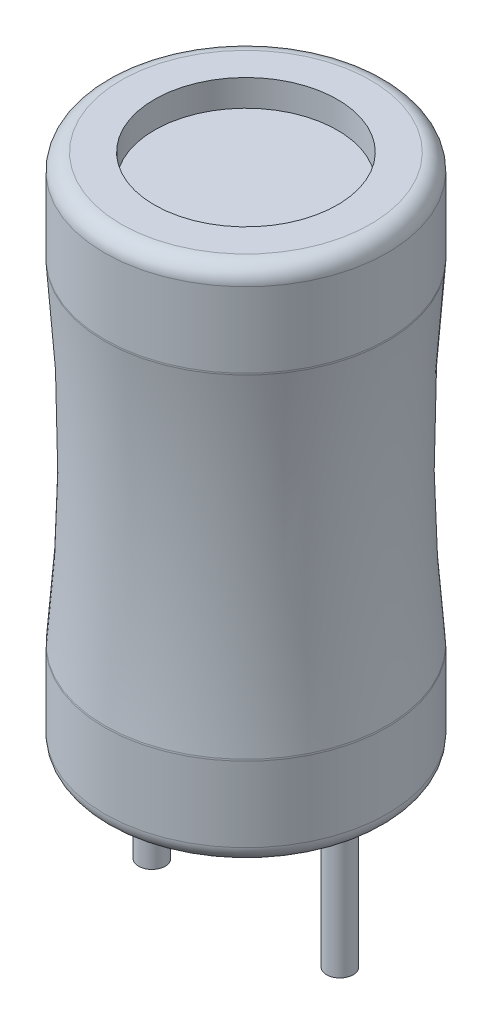
SolidWorks part; units mm, degrees
ref_plane "Front Plane" through (0, 0, 0) normal (0, 0, 1) x (1, 0, 0)
ref_plane "Top Plane" through (0, 0, 0) normal (0, 1, 0) x (1, 0, 0)
ref_plane "Right Plane" through (0, 0, 0) normal (1, 0, 0) x (0, 0, -1)
sketch "Sketch1" plane through (0, 0, 0) normal (1, 0, 0) x (0, 0, -1)
  line L0 (0, 12.5653) -> (0, 7.8) construction
  line L1 (-4.25, 7.3) -> (-4.25, 5.0494)
  line L2 (-3.75, 7.8) -> (-2.75, 7.8)
  line L3 (-54.6177, 0) -> (5.3391, 0) construction
  line L4 (-3.75, -7.8) -> (-2.75, -7.8)
  line L5 (-4.25, -7.3) -> (-4.25, -5.0494)
  line L6 (-4, 0) -> (-4, 7.8) construction
  line L7 (0, 7) -> (0, -7)
  line L8 (-2.75, 7.8) -> (-2.75, 7)
  line L9 (-2.75, 7) -> (0, 7)
  line L10 (-2.75, 7.8) -> (0, 7.8) construction
  line L11 (0, 7.8) -> (0, 7) construction
  line L12 (0, 7) -> (0, -7) construction
  line L13 (0, 7.8) -> (0, 7) construction
  line L14 (-2.75, -7) -> (0, -7)
  line L15 (-2.75, -7.8) -> (-2.75, -7)
  line L16 (-2.75, -7.8) -> (0, -7.8) construction
  line L17 (0, -7) -> (0, -7.8) construction
  line L18 (0, -7) -> (0, -7.8) construction
  line L19 (0, -7.8) -> (0, -15.4686) construction
  arc A0 (-3.75, 7.8) -> (-4.25, 7.3) centre (-3.75, 7.3) ccw
  arc A1 (-4.25, 5.0494) -> (-4.2476, 5) centre (-3.75, 5.0494) ccw
  arc A2 (-4.2476, 5) -> (-4.2476, -5) centre (-54.6177, 0) cw
  arc A3 (-3.75, -7.8) -> (-4.25, -7.3) centre (-3.75, -7.3) cw
  arc A4 (-4.25, -5.0494) -> (-4.2476, -5) centre (-3.75, -5.0494) cw
  dimension "D4" = 0.5
  dimension "D1" = 15.6
  dimension "D2" = 8.5
  dimension "D3" = 10
  dimension "D5" = 8
  dimension "D6" = 5.5
  dimension "D7" = 0.8
revolve "Revolve1" add sketch "Sketch1" angle 360 about L0
sketch "Sketch3" plane through (0, -7, 0) normal (0, -1, 0) x (1, 0, 0)
  line L0 (-2.825, 0) -> (2.825, 0) construction
  line L1 (0, -3.3096) -> (0, 3.3096) construction
  circle A0 centre (-2.825, 0) radius 0.4
  circle A1 centre (2.825, 0) radius 0.4
  point P4 (0, 0)
  point P8 (0, 0)
  dimension "D2" = 0.8
  dimension "D1" = 5.65
extrude "Boss-Extrude1" add sketch "Sketch3" along normal blind 5
